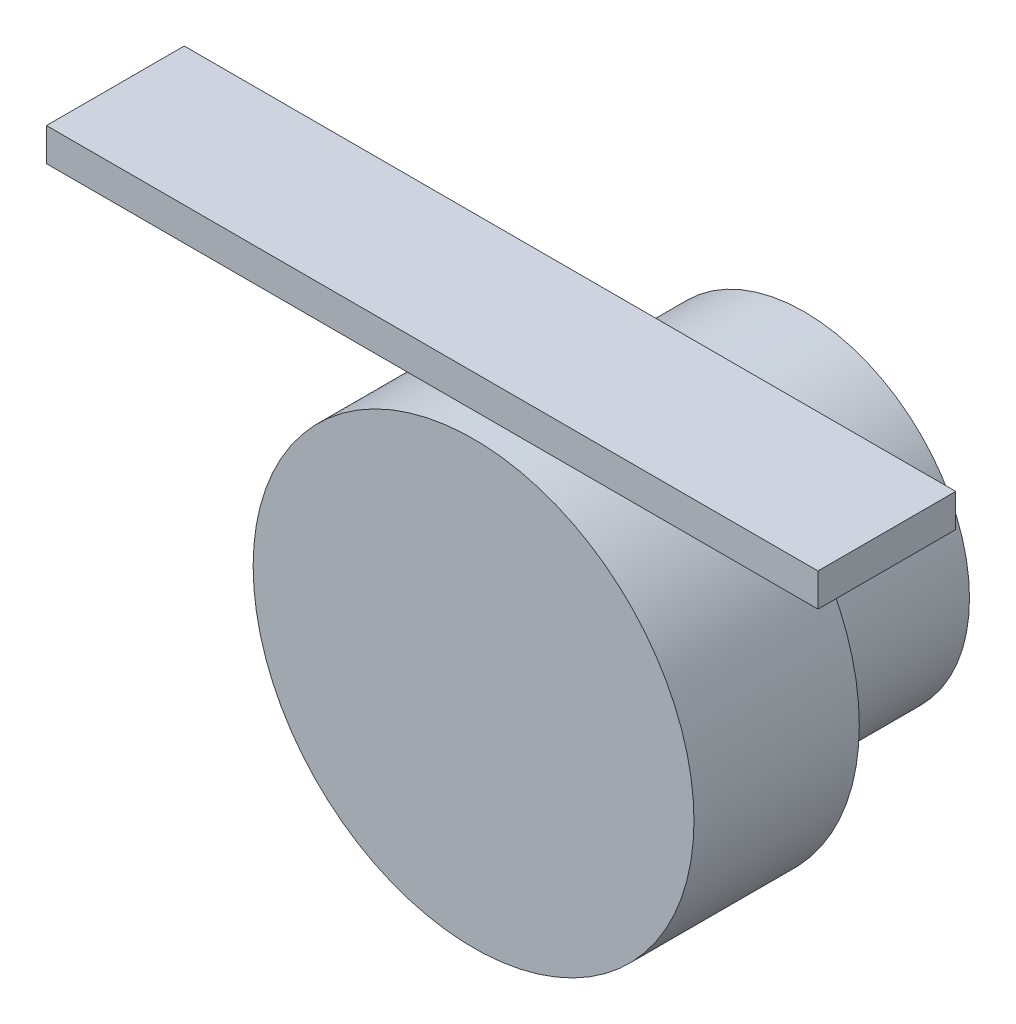
SolidWorks part; units mm, degrees
ref_plane "前视基准面" through (0, 0, 0) normal (0, 0, 1) x (1, 0, 0)
ref_plane "上视基准面" through (0, 0, 0) normal (0, 1, 0) x (1, 0, 0)
ref_plane "右视基准面" through (0, 0, 0) normal (1, 0, 0) x (0, 0, -1)
other "Configuration Table"
sketch "草图1" plane through (0, 0, 0) normal (0, 0, 1) x (1, 0, 0)
  circle A0 centre (0, 0) radius 8
extrude "top wake button cap - dia 16 mm" add sketch "草图1" along normal blind 6 from offset 3 separate body
sketch "草图2" plane through (0, 0, 0) normal (0, 0, 1) x (1, 0, 0)
  circle A0 centre (0, 0) radius 6
extrude "button threaded body / hole marker - dia 12 mm" add sketch "草图2" along normal blind 8 from offset 9 separate body
sketch "草图3" plane through (0, 0, 0) normal (0, 0, 1) x (1, 0, 0)
  line L1 (-14, 10.4) -> (14, 10.4)
  line L2 (-14, 10.4) -> (-14, 11.6)
  line L3 (-14, 11.6) -> (14, 11.6)
  line L4 (14, 10.4) -> (14, 11.6)
  line L5 (-14, 10.4) -> (14, 11.6) construction
  line L6 (-14, 11.6) -> (14, 10.4) construction
  point P0 (0, 11)
extrude "button label plate - WAKE BTN" add sketch "草图3" along normal blind 5 from offset 0.5 separate body
